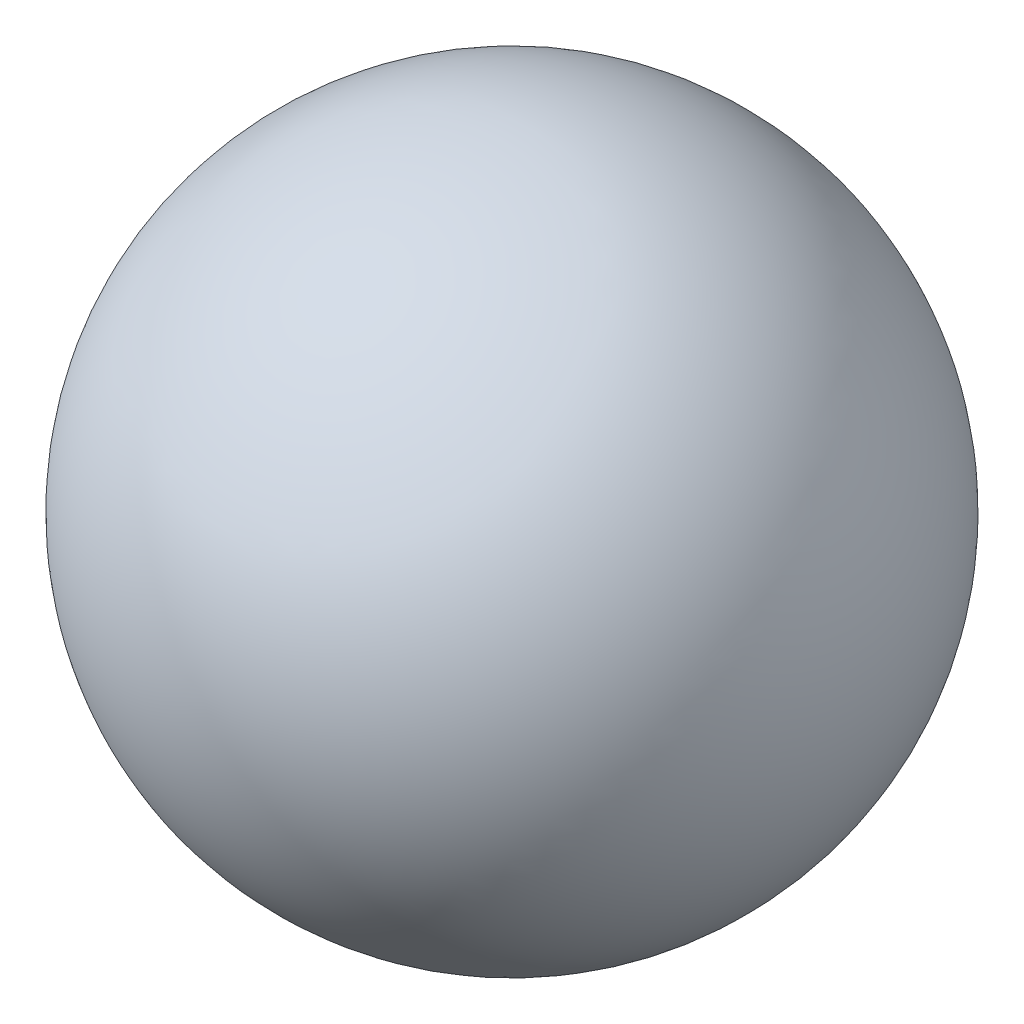
SolidWorks part; units mm, degrees
material "AISI 1010 Steel, hot rolled bar"
ref_plane "Front Plane" through (0, 0, 0) normal (0, 0, 1) x (1, 0, 0)
ref_plane "Top Plane" through (0, 0, 0) normal (0, 1, 0) x (1, 0, 0)
ref_plane "Right Plane" through (0, 0, 0) normal (1, 0, 0) x (0, 0, -1)
sketch "Sketch1" plane through (0, 0, 0) normal (0, 1, 0) x (1, 0, 0)
  line L0 (0, 3.81) -> (0, -3.81) construction
  circle A0 centre (0, 0) radius 3.81
  dimension "D1" = 7.62
revolve "Revolve2" add sketch "Sketch1" angle 360 about L0
